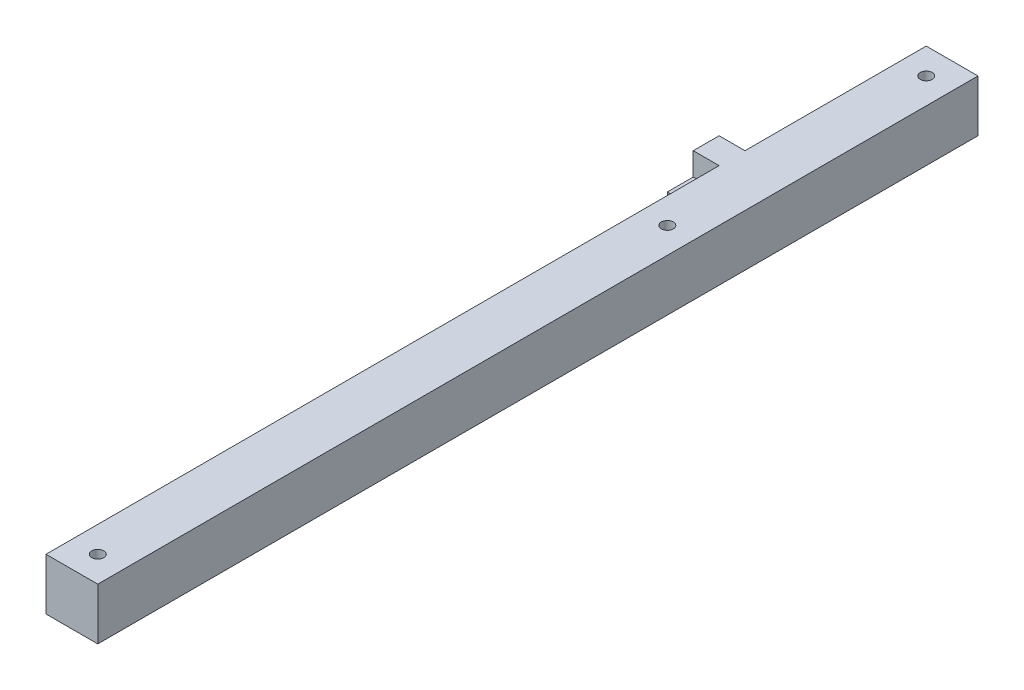
SolidWorks part; units mm, degrees
ref_plane "Front" through (0, 0, 0) normal (0, 0, 1) x (1, 0, 0)
ref_plane "Top" through (0, 0, 0) normal (0, 1, 0) x (1, 0, 0)
ref_plane "Right" through (0, 0, 0) normal (1, 0, 0) x (0, 0, -1)
sketch "Sketch18" plane through (0, 0, 0) normal (0, 1, 0) x (1, 0, 0)
  line L1 (-12.7, -12.7) -> (0, -12.7)
  line L2 (-12.7, -12.7) -> (-12.7, 203.2)
  line L3 (-12.7, 203.2) -> (0, 203.2)
  line L4 (0, -12.7) -> (0, 203.2)
  dimension "D1" = 12.7
  dimension "D2" = 12.7
  dimension "D3" = 12.7
  dimension "D4" = 215.9
extrude "Boss-Extrude3" add sketch "Sketch18" along normal blind 12.7
sketch "Sketch26" plane through (0, 12.7, 0) normal (0, 1, 0) x (1, 0, 0)
  line L0 (-6.35, -12.7) -> (-6.35, 203.2) construction
  line L1 (-12.7, -12.7) -> (0, -12.7) construction
  line L2 (0, 203.2) -> (-12.7, 203.2) construction
  point P6 (-6.35, 196.85)
  point P7 (-6.35, -6.35)
  point P8 (-6.35, 133.35)
  dimension "D1" = 6.35
  dimension "D2" = 6.35
  dimension "D3" = 63.5
hole_wizard "#32 (0.116) Diameter Hole7" positions "Sketch27" profile "Sketch28" hole size "#32" standard "ANSI Inch" end condition through all
sketch "Sketch27" plane through (0, 12.7, 0) normal (0, 1, 0) x (1, 0, 0)
  point P0 (-6.35, 196.85)
  point P3 (-6.35, 133.35)
  point P6 (-6.35, -6.35)
sketch "Sketch28" plane through (-6.35, 12.7, -196.85) normal (1, 0, 0) x (0, 0, 1)
  line L0 (0, 0) -> (0, 12.7)
  line L1 (0, 12.7) -> (1.4732, 12.7)
  line L2 (1.4732, 12.7) -> (1.4732, 0)
  line L5 (1.4732, 0) -> (0, 0)
  line L11 (0, -6.35) -> (0, 107.95) construction
  dimension "Thru Hole Dia." = 2.9464
  dimension "Thru Hole Depth" = 12.7
sketch "Sketch29" plane through (-12.7, 0, 0) normal (-1, 0, 0) x (0, 0, 1)
  line L0 (-203.2, 0) -> (12.7, 0) construction
  line L1 (-152.4, 0) -> (-158.75, 0)
  line L2 (-152.4, 0) -> (-152.4, 12.7)
  line L3 (-152.4, 12.7) -> (-158.75, 12.7)
  line L4 (-158.75, 0) -> (-158.75, 12.7)
  line L5 (-203.2, 12.7) -> (12.7, 12.7) construction
  line L6 (-203.2, 12.7) -> (-203.2, 0) construction
  dimension "D1" = 50.8
  dimension "D2" = 6.35
extrude "Boss-Extrude4" add sketch "Sketch29" along normal blind 6.35
sketch "Sketch30" plane through (-12.7, 0, 0) normal (-1, 0, 0) x (0, 0, 1)
  line L1 (-152.4, 0) -> (-146.05, 0)
  line L2 (-152.4, 0) -> (-152.4, 7.112)
  line L3 (-152.4, 7.112) -> (-146.05, 7.112)
  line L4 (-146.05, 0) -> (-146.05, 7.112)
  dimension "D1" = 7.112
  dimension "D2" = 6.35
extrude "Boss-Extrude5" add sketch "Sketch30" along normal blind 6.35
